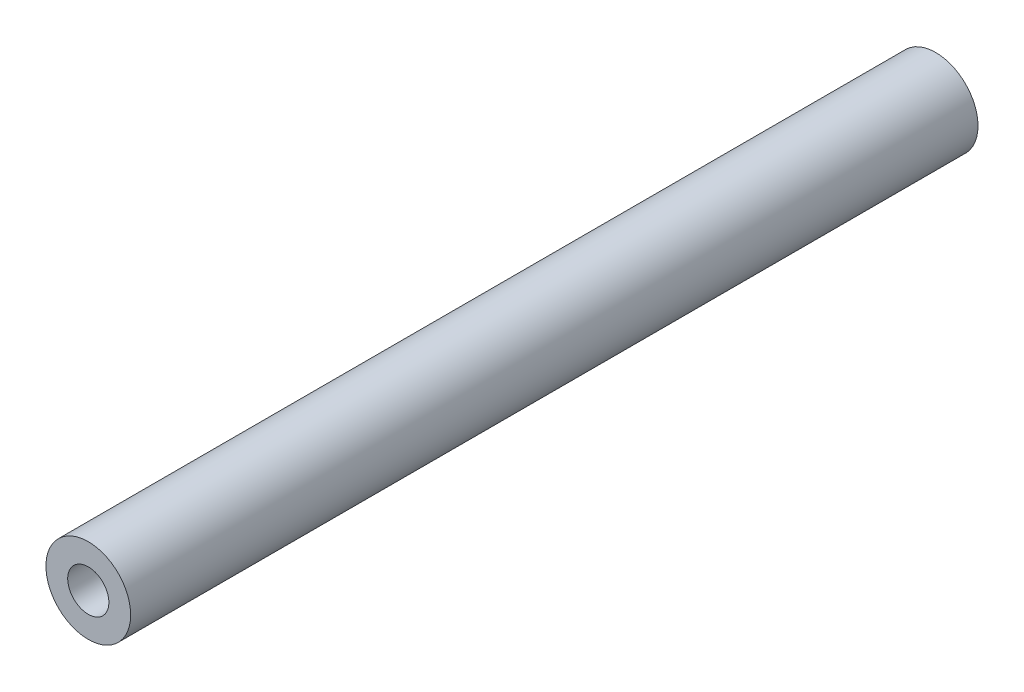
SolidWorks part; units mm, degrees
material "6061 Alloy"
ref_plane "Front Plane" through (0, 0, 0) normal (0, 0, 1) x (1, 0, 0)
ref_plane "Top Plane" through (0, 0, 0) normal (0, 1, 0) x (1, 0, 0)
ref_plane "Right Plane" through (0, 0, 0) normal (1, 0, 0) x (0, 0, -1)
sketch "Sketch1" plane through (0, 0, 0) normal (0, 0, 1) x (1, 0, 0)
  circle A0 centre (169.6384, -7.2338) radius 1.7
  circle A1 centre (169.6384, -7.2338) radius 3.5
  dimension "D1" = 3.4
  dimension "D2" = 7
extrude "Boss-Extrude1" add sketch "Sketch1" along normal blind 70
